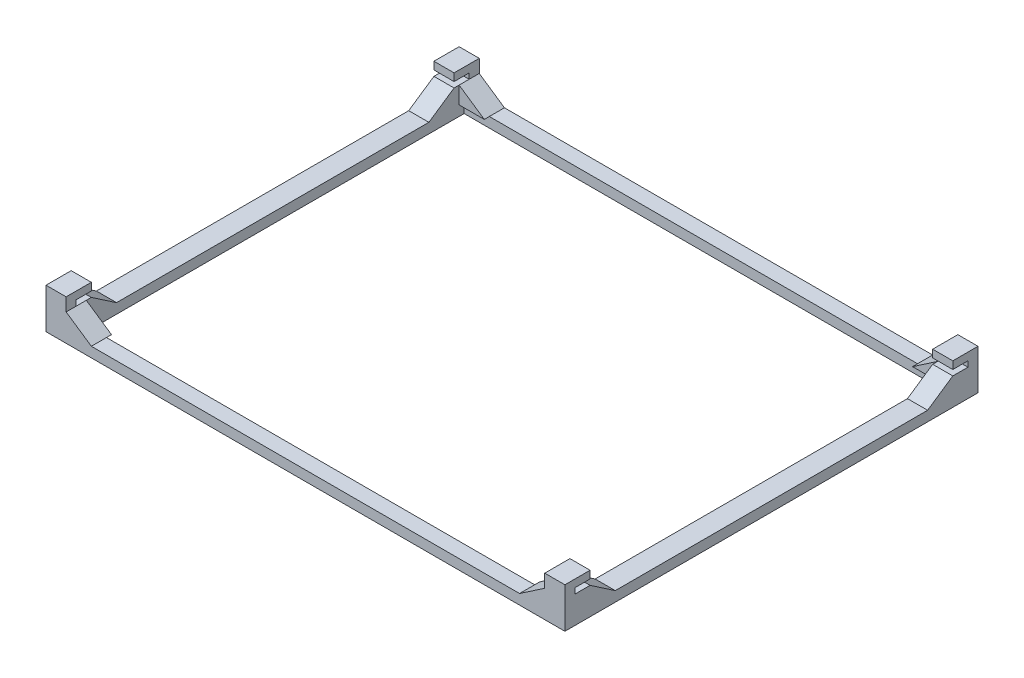
SolidWorks part; units mm, degrees
ref_plane "Спереди" through (0, 0, 0) normal (0, 0, 1) x (1, 0, 0)
ref_plane "Сверху" through (0, 0, 0) normal (0, 1, 0) x (1, 0, 0)
ref_plane "Справа" through (0, 0, 0) normal (1, 0, 0) x (0, 0, -1)
other "Configuration Table"
sketch "Эскиз1" plane through (0, 0, 0) normal (0, 1, 0) x (1, 0, 0)
  line L1 (51.5, -41) -> (-51.5, -41)
  line L2 (51.5, -41) -> (51.5, 41)
  line L3 (51.5, 41) -> (-51.5, 41)
  line L4 (-51.5, -41) -> (-51.5, 41)
  line L5 (51.5, -41) -> (-51.5, 41) construction
  line L6 (51.5, 41) -> (-51.5, -41) construction
  line L7 (47.5, -38) -> (-47.5, -38)
  line L8 (47.5, -38) -> (47.5, 38)
  line L9 (47.5, 38) -> (-47.5, 38)
  line L10 (-47.5, -38) -> (-47.5, 38)
  line L11 (47.5, -38) -> (-47.5, 38) construction
  line L12 (47.5, 38) -> (-47.5, -38) construction
  point P0 (0, 0)
  point P6 (0, 0)
  dimension "D1" = 103
  dimension "D2" = 82
  dimension "D3" = 95
  dimension "D4" = 76
  dimension "D5" = 76
extrude "Бобышка-Вытянуть2" add sketch "Эскиз1" along normal blind 2 contours L2 L1 L4 L3 | L8 L7 L10 L9
sketch "Эскиз6" plane through (51.5, 0, 0) normal (1, 0, 0) x (0, 0, -1)
  line L0 (41, 2) -> (41, 8)
  line L1 (41, 8) -> (36, 8)
  line L2 (36, 8) -> (36, 6.5)
  line L3 (36, 6.5) -> (39, 6.5)
  line L4 (39, 6.5) -> (39, 5.4)
  line L5 (39, 5.4) -> (36, 5.4)
  line L6 (36, 5.4) -> (36, 2)
  line L7 (-41, 2) -> (41, 2) construction
  line L8 (36, 2) -> (41, 2)
  line L9 (36, 5.4) -> (31, 2)
  line L10 (31, 2) -> (36, 2)
  line L11 (36, 5.4) -> (36, 2)
  line M12 (41, 2) -> (-41, 2)
  dimension "D1" = 6
  dimension "D2" = 5
  dimension "D3" = 5
  dimension "D4" = 1.5
  dimension "D5" = 1.1
  dimension "D6" = 3
  dimension "D7" = 5
extrude "Бобышка-Вытянуть3" add sketch "Эскиз6" against normal blind 4 contours L6 L9 M12 | L5 L6 L0 L1 L2 L3 L4 M12
sketch "Эскиз7" plane through (51.5, 0, 0) normal (1, 0, 0) x (0, 0, -1)
  line L0 (-41, 2) -> (-41, 8)
  line L1 (-41, 8) -> (-36, 8)
  line L2 (-36, 8) -> (-36, 6.5)
  line L3 (-36, 6.5) -> (-39, 6.5)
  line L4 (-39, 6.5) -> (-39, 5.4)
  line L5 (-39, 5.4) -> (-36, 5.4)
  line L6 (-36, 5.4) -> (-36, 2)
  line L7 (-41, 2) -> (31, 2) construction
  line L8 (-36, 2) -> (-41, 2)
  line L9 (-36, 5.4) -> (-31, 2)
  line L10 (-31, 2) -> (-36, 2)
  line L11 (-36, 5.4) -> (-36, 2)
  line M18 (31, 2) -> (-41, 2)
  dimension "D1" = 6
  dimension "D2" = 5
  dimension "D3" = 1.1
  dimension "D4" = 1.5
  dimension "D5" = 3
  dimension "D6" = 5
  dimension "D7" = 5
extrude "Бобышка-Вытянуть4" add sketch "Эскиз7" against normal blind 4 contours L6 L5 L4 L3 L2 L1 L0 M18 | L9 L6 M18
sketch "Эскиз9" plane through (-51.5, 0, 0) normal (-1, 0, 0) x (0, 0, 1)
  line L0 (-41, 2) -> (-41, 8)
  line L1 (-41, 8) -> (-36, 8)
  line L2 (-36, 8) -> (-36, 6.5)
  line L3 (-36, 8) -> (-36, 6.5) construction
  line L4 (-36, 6.5) -> (-39, 6.5)
  line L5 (-36, 6.5) -> (-39, 6.5) construction
  line L6 (-39, 6.5) -> (-39, 5.4)
  line L7 (-39, 5.4) -> (-36, 5.4)
  line L8 (-39, 5.4) -> (-36, 5.4) construction
  line L9 (-36, 5.4) -> (-36, 2)
  line L10 (41, 2) -> (-41, 2) construction
  line L11 (-36, 2) -> (-41, 2)
  line L12 (-36, 2) -> (-31, 2)
  line L13 (-31, 2) -> (-36, 5.4)
  line M4 (41, 2) -> (-41, 2)
extrude "Бобышка-Вытянуть5" add sketch "Эскиз9" against normal blind 4 contours L9 L7 L6 L4 L2 L1 L0 M4 | L13 L9 M4
sketch "Эскиз10" plane through (-51.5, 0, 0) normal (-1, 0, 0) x (0, 0, 1)
  line L0 (41, 2) -> (41, 8)
  line L1 (41, 2) -> (41, 8) construction
  line L2 (41, 8) -> (36, 8)
  line L3 (36, 8) -> (36, 6.5)
  line L4 (36, 6.5) -> (39, 6.5) construction
  line L5 (36, 6.5) -> (39, 6.5)
  line L6 (39, 6.5) -> (39, 5.4)
  line L7 (39, 5.4) -> (36, 5.4) construction
  line L8 (39, 5.4) -> (36, 5.4)
  line L9 (36, 5.4) -> (31, 2) construction
  line L10 (36, 5.4) -> (36, 2)
  line L11 (41, 2) -> (-31, 2) construction
  line L12 (36, 2) -> (31, 2)
  line L13 (31, 2) -> (36, 5.4)
  line M3 (41, 2) -> (-31, 2)
extrude "Бобышка-Вытянуть6" add sketch "Эскиз10" against normal blind 4 contours L8 L10 L0 L2 L3 L5 L6 M3 | L13 L10 M3
sketch "Эскиз11" plane through (0, 0, 41) normal (0, 0, 1) x (1, 0, 0)
  line L0 (-47.5, 2) -> (-47.5, 5.4)
  line L1 (-47.5, 5.4) -> (-42.5, 2)
  line L2 (47.5, 2) -> (-47.5, 2) construction
  line L3 (-42.5, 2) -> (-47.5, 2)
  dimension "D1" = 5
extrude "Бобышка-Вытянуть7" add sketch "Эскиз11" against normal blind 4
sketch "Эскиз12" plane through (0, 0, 41) normal (0, 0, 1) x (1, 0, 0)
  line L0 (47.5, 2) -> (47.5, 5.4)
  line L1 (47.5, 5.4) -> (42.5, 2)
  line L2 (47.5, 2) -> (-42.5, 2) construction
  line L3 (42.5, 2) -> (47.5, 2)
  dimension "D1" = 5
extrude "Бобышка-Вытянуть8" add sketch "Эскиз12" against normal blind 4
sketch "Эскиз13" plane through (0, 0, -41) normal (0, 0, -1) x (-1, 0, 0)
  line L0 (-47.5, 2) -> (-47.5, 5.4)
  line L1 (-47.5, 5.4) -> (-42.5, 2) construction
  line L2 (-47.5, 2) -> (-47.5, 5.4) construction
  line L3 (-47.5, 5.4) -> (-42.5, 2)
  line L4 (-47.5, 2) -> (47.5, 2) construction
  line L5 (-42.5, 2) -> (-47.5, 2) construction
  line L6 (-42.5, 2) -> (-47.5, 2)
  dimension "D1" = 5
extrude "Бобышка-Вытянуть9" add sketch "Эскиз13" against normal blind 4
sketch "Эскиз14" plane through (0, 0, -41) normal (0, 0, -1) x (-1, 0, 0)
  line L0 (47.5, 2) -> (47.5, 5.4)
  line L1 (47.5, 5.4) -> (42.5, 2)
  line L2 (42.5, 2) -> (47.5, 2)
extrude "Бобышка-Вытянуть10" add sketch "Эскиз14" against normal blind 4
